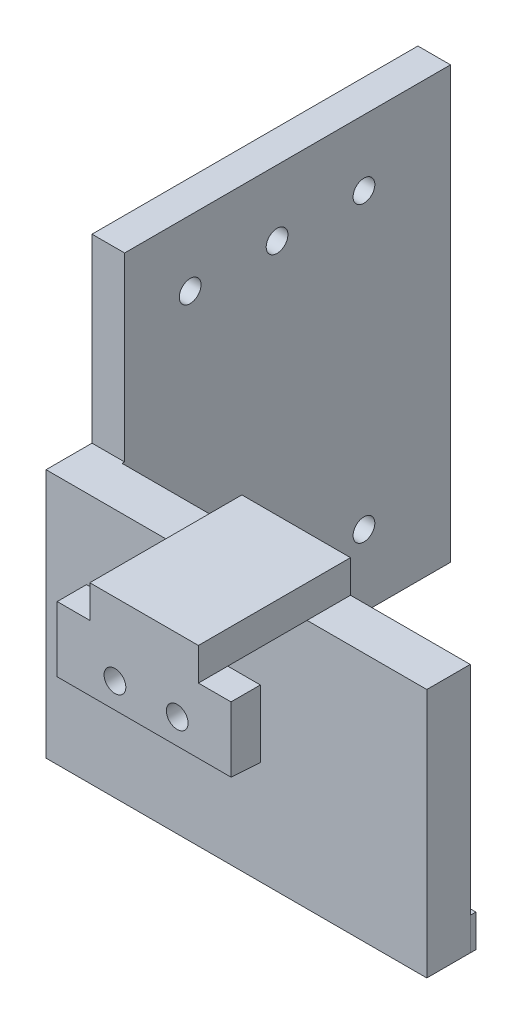
SolidWorks part; units mm, degrees
ref_plane "Plan de face" through (0, 0, 0) normal (0, 0, 1) x (1, 0, 0)
ref_plane "Plan de dessus" through (0, 0, 0) normal (0, 1, 0) x (1, 0, 0)
ref_plane "Plan de droite" through (0, 0, 0) normal (1, 0, 0) x (0, 0, -1)
sketch "Esquisse1" plane through (0, 0, 0) normal (0, 1, 0) x (1, 0, 0)
  line L0 (-38.9592, 34.6304) -> (-6.7592, 34.6304)
  line L1 (-6.9092, 10.1098) -> (-6.9092, 15.1098) construction
  line L2 (-23.0092, 10.1098) -> (-23.0092, 15.1098)
  line L3 (-9.5092, 16.1098) -> (-9.5092, 22.1098)
  line L4 (-35.5092, 15.1098) -> (-10.5092, 15.1098)
  line L5 (-10.5092, 15.1098) -> (-9.5092, 15.1098)
  line L6 (-35.5092, 15.1098) -> (-36.5092, 15.1098)
  line L7 (-36.5092, 16.1098) -> (-36.5092, 22.1098)
  line L8 (-9.5092, 22.1098) -> (-9.5092, 23.1098)
  line L9 (-36.5092, 22.1098) -> (-36.5092, 23.1098)
  line L10 (-36.5092, 23.1098) -> (-36.5092, 24.1098)
  line L11 (-9.5092, 23.1098) -> (-9.5092, 24.1098)
  line L12 (-36.5092, 22.1098) -> (-9.5092, 22.1098)
  line L13 (-36.5092, 24.1098) -> (-36.5092, 30.1098)
  line L14 (-9.5092, 24.1098) -> (-9.5092, 30.1098)
  line L15 (-9.5092, 30.1098) -> (-9.5092, 31.1098)
  line L16 (-36.5092, 30.1098) -> (-36.5092, 31.1098)
  line L17 (-38.9592, 34.6304) -> (-38.9592, 10.1098)
  line L18 (-38.9592, 10.1098) -> (-6.9092, 10.1098)
  line L19 (-6.9092, 10.1098) -> (-6.7592, 34.6304)
  circle A0 centre (-36.5092, 15.1098) radius 1
  circle A1 centre (-9.5092, 15.1098) radius 1
  circle A2 centre (-36.5092, 23.1098) radius 1
  circle A3 centre (-9.5092, 23.1098) radius 1
  circle A4 centre (-36.5092, 31.1098) radius 1
  circle A5 centre (-9.5092, 31.1098) radius 1
  point P9 (-23.0092, 15.1098)
  dimension "D1" = 25
  dimension "D2" = 1
  dimension "D3" = 1
  dimension "D4" = 6
extrude "Boss.-Extru.1" add sketch "Esquisse1" along normal blind 3
sketch "Esquisse2" plane through (0, 0, -10.1098) normal (0, 0, 1) x (1, 0, 0)
  line L0 (-38.9592, 3) -> (-6.9092, 3)
  line L1 (-6.9092, 3) -> (-6.9092, 0)
  line L2 (-6.9092, 0) -> (-38.9592, 0)
  line L3 (-38.9592, 0) -> (-38.9592, 3)
extrude "Boss.-Extru.2" add sketch "Esquisse2" along normal blind 4
sketch "Esquisse3" plane through (0, 3, 0) normal (0, 1, 0) x (1, 0, 0)
  line L0 (-38.9592, 6.1098) -> (-6.9092, 6.1098)
  line L1 (-6.9092, 6.1098) -> (-6.9092, 10.1098)
  line L2 (-6.9092, 10.1098) -> (-38.9592, 10.1098)
  line L3 (-38.9592, 34.6304) -> (-38.9592, 6.1098) construction
  line L4 (-38.9592, 10.1098) -> (-38.9592, 6.1098)
extrude "Boss.-Extru.3" add sketch "Esquisse3" along normal blind 20 contours L4 L0 L1 L2
sketch "Esquisse4" plane through (0, 0, -6.1098) normal (0, 0, 1) x (1, 0, 0)
  line L0 (-22.9342, 23) -> (-17.9342, 23)
  line L1 (-38.9592, 23) -> (-6.9092, 23) construction
  line L2 (-22.9342, 23) -> (-27.9342, 23)
  line L3 (-27.9342, 23) -> (-27.9342, 26)
  line L4 (-27.9342, 26) -> (-17.9342, 26)
  line L5 (-17.9342, 26) -> (-17.9342, 23)
extrude "Boss.-Extru.4" add sketch "Esquisse4" along normal blind 10 and the other way blind 4
sketch "Esquisse5" plane through (0, 23, 0) normal (0, -1, 0) x (1, 0, 0)
  line L0 (-27.9342, 3.8902) -> (-17.9342, 3.8902)
  line L1 (-27.9342, 3.8902) -> (-17.9342, 3.8902) construction
  line L2 (-17.9342, 3.8902) -> (-17.9342, 1.1887)
  line L3 (-17.9342, -6.1098) -> (-17.9342, 3.8902) construction
  line L4 (-17.9342, 1.1887) -> (-27.9342, 1.1887)
  line L5 (-27.9342, -6.1098) -> (-27.9342, 3.8902) construction
  line L6 (-27.9342, 1.1887) -> (-27.9342, 3.8902)
extrude "Boss.-Extru.5" add sketch "Esquisse5" along normal blind 6
sketch "Esquisse6" plane through (-17.9342, 0, 0) normal (1, 0, 0) x (0, 0, -1)
  line L0 (-1.1887, 23) -> (-3.8902, 23)
  line L1 (-3.8902, 17) -> (-3.8902, 26) construction
  line L2 (-3.8902, 23) -> (-3.8902, 17)
  line L3 (-3.8902, 17) -> (-1.1887, 16.8137)
  line L4 (-1.1887, 16.8137) -> (-1.1887, 23)
extrude "Boss.-Extru.6" add sketch "Esquisse6" along normal blind 3
sketch "Esquisse7" plane through (-27.9342, 0, 0) normal (-1, 0, 0) x (0, 0, 1)
  line L0 (3.8902, 17) -> (1.1887, 17)
  line L1 (1.1887, 17) -> (1.1887, 23)
  line L2 (1.1887, 17) -> (1.1887, 23) construction
  line L3 (1.1887, 23) -> (3.8902, 23)
  line L4 (3.8902, 26) -> (3.8902, 17) construction
  line L5 (3.8902, 23) -> (3.8902, 17)
extrude "Boss.-Extru.7" add sketch "Esquisse7" along normal blind 3
sketch "Esquisse8" plane through (0, 0, 3.8902) normal (0, 0, 1) x (1, 0, 0)
  line L0 (-27.5669, 17) -> (-17.9342, 17)
  line L2 (-27.5669, 17) -> (-27.5669, 19.3234)
  line L3 (-27.5669, 19.3234) -> (-25.6169, 19.3234)
  line L4 (-17.9342, 17) -> (-17.9342, 19.3234)
  line L5 (-17.9342, 19.3234) -> (-19.8842, 19.3234)
  circle A0 centre (-25.6169, 19.3234) radius 1
  circle A1 centre (-19.8842, 19.3234) radius 1
  point P3 (-22.7506, 17)
extrude "Enlèv. mat.-Extru.1" cut sketch "Esquisse8" against normal blind 5
sketch "Esquisse9" plane through (0, 0, -34.6304) normal (0, 0, -1) x (-1, 0, 0)
  line L0 (6.7592, 0) -> (6.7592, 3)
  line L1 (6.7592, 0) -> (39.1543, 0)
  line L2 (6.7592, 3) -> (39.1543, 3)
  line L3 (39.1543, 0) -> (39.1543, 3)
  line L4 (38.9592, 3) -> (6.7592, 3) construction
  line L5 (6.7592, 3) -> (6.7592, 0) construction
extrude "Enlèv. mat.-Extru.2" cut sketch "Esquisse9" against normal blind 24
sketch "Esquisse10" plane through (-38.9592, 0, 0) normal (-1, 0, 0) x (0, 0, 1)
  line L0 (-6.1098, 0) -> (-6.1098, 23)
  line L1 (-6.1098, 0) -> (-10.34, 0)
  line L2 (-6.1098, 23) -> (-10.34, 23)
  line L3 (-10.34, 0) -> (-10.34, 23)
extrude "Boss.-Extru.8" add sketch "Esquisse10" along normal blind 3
sketch "Esquisse11" plane through (0, 0, -10.34) normal (0, 0, -1) x (-1, 0, 0)
  line L0 (38.9592, 0) -> (41.9592, 0)
  line L1 (38.9592, 0) -> (38.9592, 39.6617)
  line L2 (41.9592, 0) -> (41.9592, 39.6617)
  line L3 (38.9592, 39.6617) -> (41.9592, 39.6617)
extrude "Boss.-Extru.9" add sketch "Esquisse11" along normal blind 30
sketch "Esquisse12" plane through (-41.9592, -0.1427, -42.3261) normal (-1, 0, 0) x (0, -1, 0)
  line L13 (-6.7531, 10.9515) -> (-6.7531, 16.9515)
  line L14 (-32.7531, 9.9515) -> (-7.7531, 9.9515)
  line L15 (-7.7531, 9.9515) -> (-6.7531, 9.9515)
  line L16 (-32.7531, 9.9515) -> (-33.7531, 9.9515)
  line L17 (-33.7531, 10.9515) -> (-33.7531, 16.9515)
  line L18 (-6.7531, 16.9515) -> (-6.7531, 17.9515)
  line L19 (-33.7531, 16.9515) -> (-33.7531, 17.9515)
  line L20 (-33.7531, 17.9515) -> (-33.7531, 18.9515)
  line L21 (-6.7531, 17.9515) -> (-6.7531, 18.9515)
  line L22 (-33.7531, 16.9515) -> (-6.7531, 16.9515)
  line L23 (-33.7531, 18.9515) -> (-33.7531, 24.9515)
  line L24 (-6.7531, 18.9515) -> (-6.7531, 24.9515)
  line L25 (-6.7531, 24.9515) -> (-6.7531, 25.9515)
  line L30 (-33.7531, 24.9515) -> (-33.7531, 25.9515)
  circle A15 centre (-33.7531, 9.9515) radius 1
  circle A16 centre (-6.7531, 9.9515) radius 1
  circle A17 centre (-33.7531, 17.9515) radius 1
  circle A18 centre (-6.7531, 17.9515) radius 1
  circle A19 centre (-33.7531, 25.9515) radius 1
  circle A20 centre (-6.7531, 25.9515) radius 1
  point P0 (0, 0)
  point P36 (-20.2531, 9.9515)
  dimension "D5" = 1
  dimension "D8" = 1
  dimension "D10" = 6
  dimension "D2" = 25
  dimension "D9" = 6
  dimension "D11" = 6
  dimension "D12" = 6
extrude "Enlèv. mat.-Extru.3" cut sketch "Esquisse12" against normal blind 30
